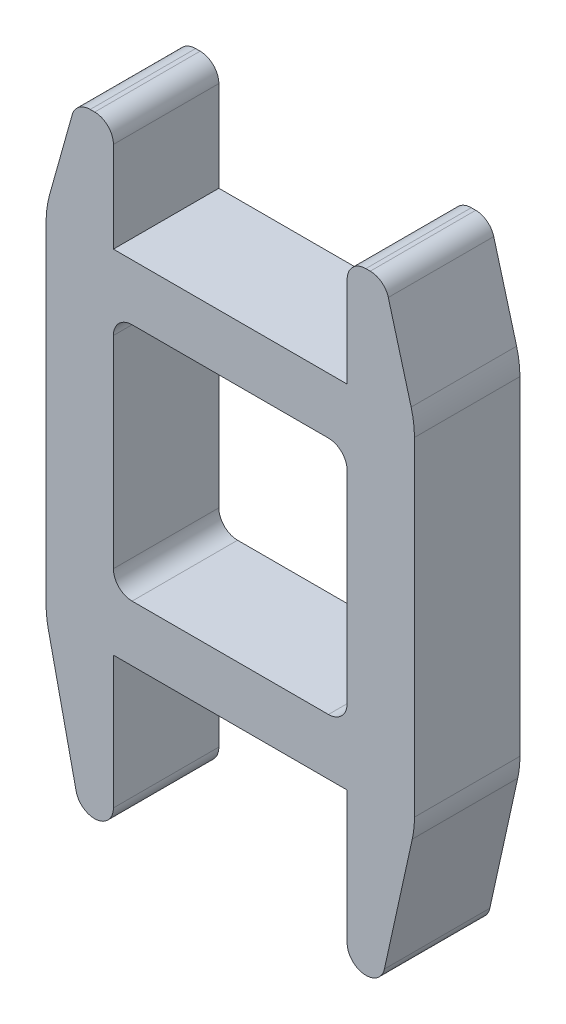
SolidWorks part; units mm, degrees
material "Acrylic (Medium-high impact)"
ref_plane "Front Plane" through (0, 0, 0) normal (0, 0, 1) x (1, 0, 0)
ref_plane "Top Plane" through (0, 0, 0) normal (0, 1, 0) x (1, 0, 0)
ref_plane "Right Plane" through (0, 0, 0) normal (1, 0, 0) x (0, 0, -1)
sketch "Sketch1" plane through (0, 0, 0) normal (0, 0, 1) x (1, 0, 0)
  line L0 (1247.1596, 961.2772) -> (1247.1596, 950.4772)
  line L1 (1263.2596, 947.9772) -> (1243.5596, 947.9772) construction
  line L2 (1247.1596, 946.4772) -> (1243.5596, 946.4772) construction
  line L3 (1248.1596, 962.2772) -> (1258.6596, 962.2772)
  line L4 (1245.9178, 971.1264) -> (1246.1596, 971.1264)
  line L5 (1247.1596, 970.1264) -> (1247.1596, 965.2772)
  line L6 (1247.1596, 955.8772) -> (1259.6596, 955.8772) construction
  line L7 (1259.6596, 965.2772) -> (1247.1596, 965.2772)
  line L8 (1243.5596, 964.7327) -> (1243.5596, 947.0217)
  line L9 (1243.6768, 945.9455) -> (1245.1674, 939.1828)
  line L10 (1247.1596, 965.2772) -> (1243.5596, 965.2772) construction
  line L11 (1259.6596, 946.4772) -> (1247.1596, 946.4772)
  line L12 (1243.7453, 966.0827) -> (1244.9549, 970.3964)
  line L13 (1247.1596, 939.398) -> (1247.1596, 946.4772)
  line L14 (1246.144, 938.398) -> (1246.1596, 938.398)
  line L15 (1248.1596, 949.4772) -> (1258.6596, 949.4772)
  line L16 (1259.6596, 965.2772) -> (1263.2596, 965.2772) construction
  line L17 (1259.6596, 946.4772) -> (1263.2596, 946.4772) construction
  line L18 (1260.6753, 938.398) -> (1260.6596, 938.398)
  line L19 (1253.4096, -39.6851) -> (1253.4096, 49960.3149) construction
  line L20 (1259.6596, 939.398) -> (1259.6596, 946.4772)
  line L21 (1263.0824, 965.9249) -> (1261.861, 970.3902)
  line L22 (1263.1424, 945.9455) -> (1261.6519, 939.1828)
  line L23 (1263.2596, 964.6057) -> (1263.2596, 947.0217)
  line L24 (1259.6596, 970.1264) -> (1259.6596, 965.2772)
  line L25 (1260.8964, 971.1264) -> (1260.6596, 971.1264)
  line L26 (1263.2596, 963.7772) -> (1243.5596, 963.7772) construction
  line L27 (1259.6596, 961.2772) -> (1259.6596, 950.4772)
  arc A0 (1247.1596, 961.2772) -> (1248.1596, 962.2772) centre (1248.1596, 961.2772) cw
  arc A1 (1258.6596, 962.2772) -> (1259.6596, 961.2772) centre (1258.6596, 961.2772) cw
  arc A2 (1258.6596, 949.4772) -> (1259.6596, 950.4772) centre (1258.6596, 950.4772) ccw
  arc A3 (1248.1596, 949.4772) -> (1247.1596, 950.4772) centre (1248.1596, 950.4772) cw
  arc A4 (1246.144, 938.398) -> (1245.1674, 939.1828) centre (1246.144, 939.398) cw
  arc A5 (1246.1596, 938.398) -> (1247.1596, 939.398) centre (1246.1596, 939.398) ccw
  arc A6 (1260.6753, 938.398) -> (1261.6519, 939.1828) centre (1260.6753, 939.398) ccw
  arc A7 (1260.6596, 938.398) -> (1259.6596, 939.398) centre (1260.6596, 939.398) cw
  arc A8 (1260.8964, 971.1264) -> (1261.861, 970.3902) centre (1260.8964, 970.1264) cw
  arc A9 (1260.6596, 971.1264) -> (1259.6596, 970.1264) centre (1260.6596, 970.1264) ccw
  arc A10 (1247.1596, 970.1264) -> (1246.1596, 971.1264) centre (1246.1596, 970.1264) ccw
  arc A11 (1245.9178, 971.1264) -> (1244.9549, 970.3964) centre (1245.9178, 970.1264) ccw
  arc A12 (1263.2596, 964.6057) -> (1263.0824, 965.9249) centre (1258.2596, 964.6057) ccw
  arc A13 (1243.7453, 966.0827) -> (1243.5596, 964.7327) centre (1248.5596, 964.7327) ccw
  arc A14 (1243.5596, 947.0217) -> (1243.6768, 945.9455) centre (1248.5596, 947.0217) ccw
  arc A15 (1263.2596, 947.0217) -> (1263.1424, 945.9455) centre (1258.2596, 947.0217) cw
  point P2 (1263.2596, 955.8772)
  point P14 (1243.5596, 955.8772)
  point P15 (1253.4096, 965.2772)
  point P20 (1253.4096, 963.7772)
  point P26 (1253.4096, 955.8772)
  point P28 (1253.4096, 965.2772)
  point P30 (1253.4096, 962.2772)
  point P31 (1253.4096, 947.9772)
  point P33 (1253.4096, 949.4772)
  point P36 (1253.4096, 946.4772)
  point P38 (1253.4096, 962.2772)
  point P41 (1247.1596, 962.2772)
  point P44 (1259.6596, 962.2772)
  point P47 (1259.6596, 949.4772)
  point P50 (1247.1596, 949.4772)
  point P53 (1245.3404, 938.398)
  point P56 (1247.1596, 938.398)
  point P59 (1261.4789, 938.398)
  point P62 (1259.6596, 938.398)
  point P65 (1261.6596, 971.1264)
  point P68 (1259.6596, 971.1264)
  point P71 (1247.1596, 971.1264)
  point P74 (1245.1596, 971.1264)
  dimension "D9" = 1
  dimension "D10" = 5
  dimension "D11" = 5
  dimension "D1" = 6.25
  dimension "D2" = 5.8492
  dimension "D3" = 2
  dimension "D4" = 3
  dimension "D5" = 9.4
  dimension "D6" = 8.0792
  dimension "D7" = 192.43
  dimension "D8" = 3.6
extrude "Boss-Extrude1" add sketch "Sketch1" along normal blind 5.64
